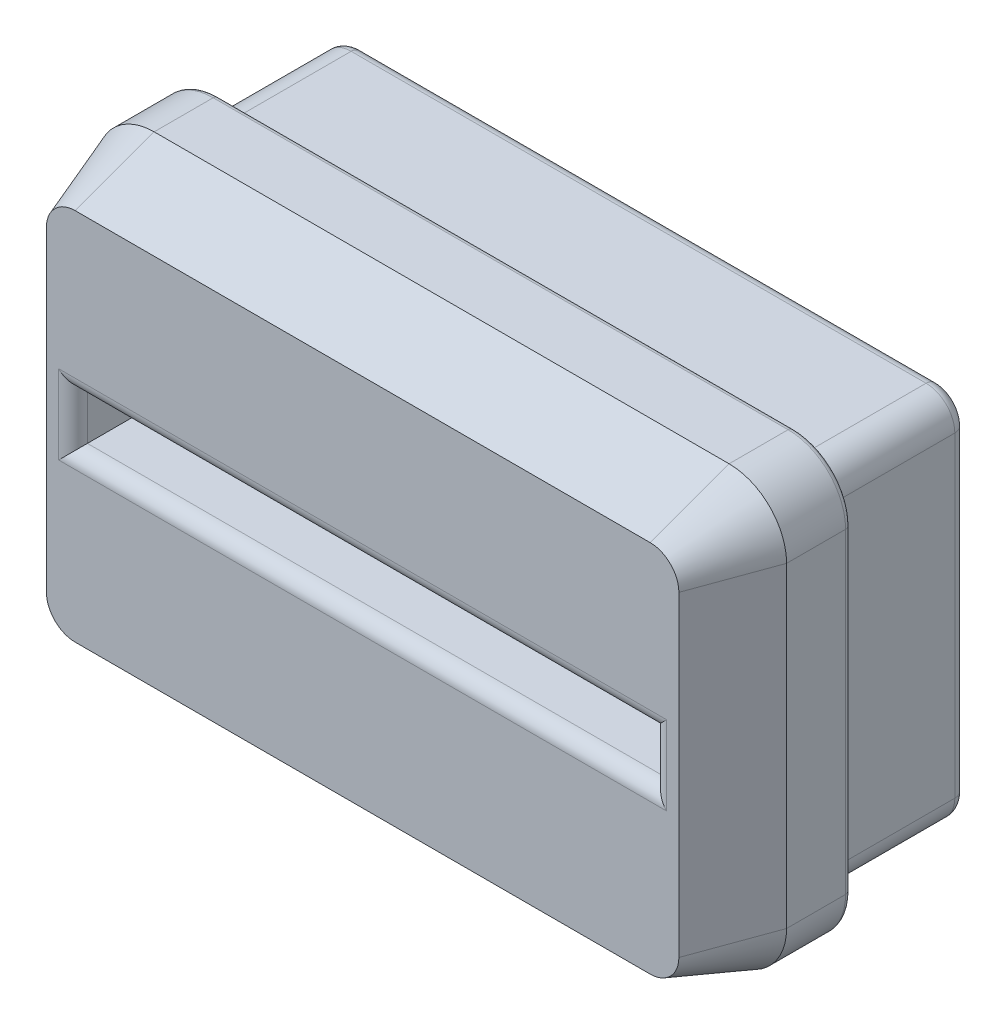
SolidWorks part; units mm, degrees
ref_plane "Front Plane" through (0, 0, 0) normal (0, 0, 1) x (1, 0, 0)
ref_plane "Top Plane" through (0, 0, 0) normal (0, 1, 0) x (1, 0, 0)
ref_plane "Right Plane" through (0, 0, 0) normal (1, 0, 0) x (0, 0, -1)
sketch "Sketch1" plane through (0, 0, 0) normal (0, 1, 0) x (1, 0, 0)
  line L1 (-12, 6.5) -> (12, 6.5)
  line L2 (-12, 6.5) -> (-12, -6.5)
  line L3 (-12, -6.5) -> (12, -6.5)
  line L4 (12, 6.5) -> (12, -6.5)
  line L5 (-12, 6.5) -> (12, -6.5) construction
  line L6 (-12, -6.5) -> (12, 6.5) construction
  point P0 (0, 0)
  dimension "D1" = 24
  dimension "D2" = 13
extrude "Boss-Extrude1" add sketch "Sketch1" along normal blind 15
sketch "Sketch2" plane through (0, 0, 6.5) normal (0, 0, 1) x (1, 0, 0)
  line L0 (0, 0) -> (0, 15) construction
  line L1 (-12, 15) -> (12, 15) construction
  line L2 (-12, 0) -> (12, 0) construction
  line L3 (-10.075, 8.45) -> (10.075, 8.45)
  line L4 (-10.075, 8.45) -> (-10.075, 6.7)
  line L5 (-10.075, 6.7) -> (10.075, 6.7)
  line L6 (10.075, 8.45) -> (10.075, 6.7)
  line L7 (-10.075, 8.45) -> (10.075, 6.7) construction
  line L8 (-10.075, 6.7) -> (10.075, 8.45) construction
  point P5 (0, 7.575)
  dimension "D1" = 6.7
  dimension "D2" = 1.75
  dimension "D3" = 20.15
extrude "Cut-Extrude1" cut sketch "Sketch2" against normal blind 15
fillet "Fillet1" radius 2 4 edges at (12, 15, 0) (12, 0, 0) (-12, 0, 0) (-12, 15, 0)
chamfer "Chamfer2" distance 1 angle 70 8 edges at (0, 0, 6.5) (-11.4142, 0.5858, 6.5) (11.4142, 0.5858, 6.5) (-12, 7.5, 6.5) (12, 7.5, 6.5) (-11.4142, 14.4142, 6.5) (11.4142, 14.4142, 6.5) (0, 15, 6.5)
fillet "Fillet2" radius 0.5 4 edges at (10.075, 7.575, 6.5) (0, 8.45, 6.5) (-10.075, 7.575, 6.5) (0, 6.7, 6.5)
sketch "Sketch4" plane through (0, 0, -6.5) normal (0, 0, -1) x (-1, 0, 0)
  line L0 (-10.075, 8.45) -> (-8.575, 8.45)
  line L1 (-10.075, 6.7) -> (10.075, 6.7)
  line L2 (-10.075, 6.7) -> (-10.075, 8.45)
  line L3 (-8.575, 11.8912) -> (8.575, 11.8912)
  line L4 (10.075, 6.7) -> (10.075, 8.45)
  line L5 (-10.075, 8.45) -> (10.075, 8.45) construction
  line L6 (-8.575, 8.45) -> (-8.575, 11.8912)
  line L7 (10.075, 8.45) -> (8.575, 8.45)
  line L8 (8.575, 8.45) -> (8.575, 11.8912)
  dimension "D2" = 1.5
  dimension "D3" = 1.5
extrude "Cut-Extrude4" cut sketch "Sketch4" against normal blind 11
sketch "Sketch5" plane through (0, 0, -6.5) normal (0, 0, -1) x (-1, 0, 0)
  line L5 (-13.5112, 17.4159) -> (13.3444, 17.4159)
  line L6 (-13.5112, 17.4159) -> (-13.5112, -1.8918)
  line L7 (-13.5112, -1.8918) -> (13.3444, -1.8918)
  line L8 (10, 14) -> (-10, 14)
  line L9 (-11, 13) -> (-11, 2)
  line L10 (-10, 1) -> (10, 1)
  line L11 (11, 2) -> (11, 13)
  line L12 (10, 14) -> (-10, 14)
  line L13 (-11, 13) -> (-11, 2)
  line L14 (-10, 1) -> (10, 1)
  line L15 (11, 2) -> (11, 13)
  line L16 (13.3444, 17.4159) -> (13.3444, -1.8918)
  arc A8 (-10, 14) -> (-11, 13) centre (-10, 13) ccw
  arc A9 (-11, 2) -> (-10, 1) centre (-10, 2) ccw
  arc A10 (10, 1) -> (11, 2) centre (10, 2) ccw
  arc A11 (11, 13) -> (10, 14) centre (10, 13) ccw
  arc A12 (-10, 14) -> (-11, 13) centre (-10, 13) ccw
  arc A13 (-11, 2) -> (-10, 1) centre (-10, 2) ccw
  arc A14 (10, 1) -> (11, 2) centre (10, 2) ccw
  arc A15 (11, 13) -> (10, 14) centre (10, 13) ccw
  dimension "D1" = 1
extrude "Cut-Extrude5" cut sketch "Sketch5" against normal blind 8
sketch "Sketch6" plane through (0, 0, -6.5) normal (0, 0, -1) x (-1, 0, 0)
  line L8 (-9, 5.7) -> (9, 5.7)
  line L9 (10.075, 6.7) -> (-10.075, 6.7) construction
  line L12 (10, 13) -> (-10, 13)
  line L13 (-10, 13) -> (-10, 2)
  line L14 (-10, 2) -> (10, 2)
  line L15 (10, 2) -> (10, 13)
  line L17 (-10, 4.7) -> (-10, 3)
  line L18 (-9, 2) -> (9, 2)
  line L19 (10, 3) -> (10, 4.7)
  arc A8 (9, 2) -> (10, 3) centre (9, 3) ccw
  arc A9 (9, 5.7) -> (10, 4.7) centre (9, 4.7) cw
  arc A10 (-10, 3) -> (-9, 2) centre (-9, 3) ccw
  arc A11 (-9, 5.7) -> (-10, 4.7) centre (-9, 4.7) ccw
  dimension "D3" = 1
  dimension "D2" = 1
  dimension "D1" = 1
extrude "Cut-Extrude6" cut sketch "Sketch6" against normal blind 11
sketch "Sketch7" plane through (0, 0, -6.5) normal (0, 0, -1) x (-1, 0, 0)
  line L1 (-14.3755, 18.0591) -> (15.6072, 18.0591)
  line L2 (-14.3755, 18.0591) -> (-14.3755, -3.4999)
  line L3 (-14.3755, -3.4999) -> (15.6072, -3.4999)
  line L4 (15.6072, 18.0591) -> (15.6072, -3.4999)
extrude "Cut-Extrude7" cut sketch "Sketch7" against normal blind 3
chamfer "Chamfer3" distance 2 angle 45 2 edges at (9.325, 8.45, -3.5) (-9.325, 8.45, -3.5)
fillet "Fillet3" radius 0.4 22 edges at (-9.7071, 5.4071, -3.5) (0, 5.7, -3.5) (9.7071, 5.4071, -3.5) (10, 3.85, -3.5) (9.7071, 2.2929, -3.5) (0, 2, -3.5) (-9.7071, 2.2929, -3.5) (10.7071, 13.7071, -3.5) (11, 7.5, -3.5) (10.7071, 1.2929, -3.5) (0, 1, -3.5) (-10.7071, 1.2929, -3.5) (-11, 7.5, -3.5) (-10.7071, 13.7071, -3.5) (9.325, 10.45, -3.5) (8.575, 11.1706, -3.5) (-9.325, 10.45, -3.5) (-8.575, 11.1706, -3.5) (0, 11.8912, -3.5) (0, 6.7, -3.5) (-10, 3.85, -3.5) (0, 14, -3.5)
fillet "Fillet4" radius 0.2 8 edges at (0, 15, 1.5) (11.4142, 14.4142, 1.5) (12, 7.5, 1.5) (11.4142, 0.5858, 1.5) (0, 0, 1.5) (-11.4142, 0.5858, 1.5) (-12, 7.5, 1.5) (-11.4142, 14.4142, 1.5)
